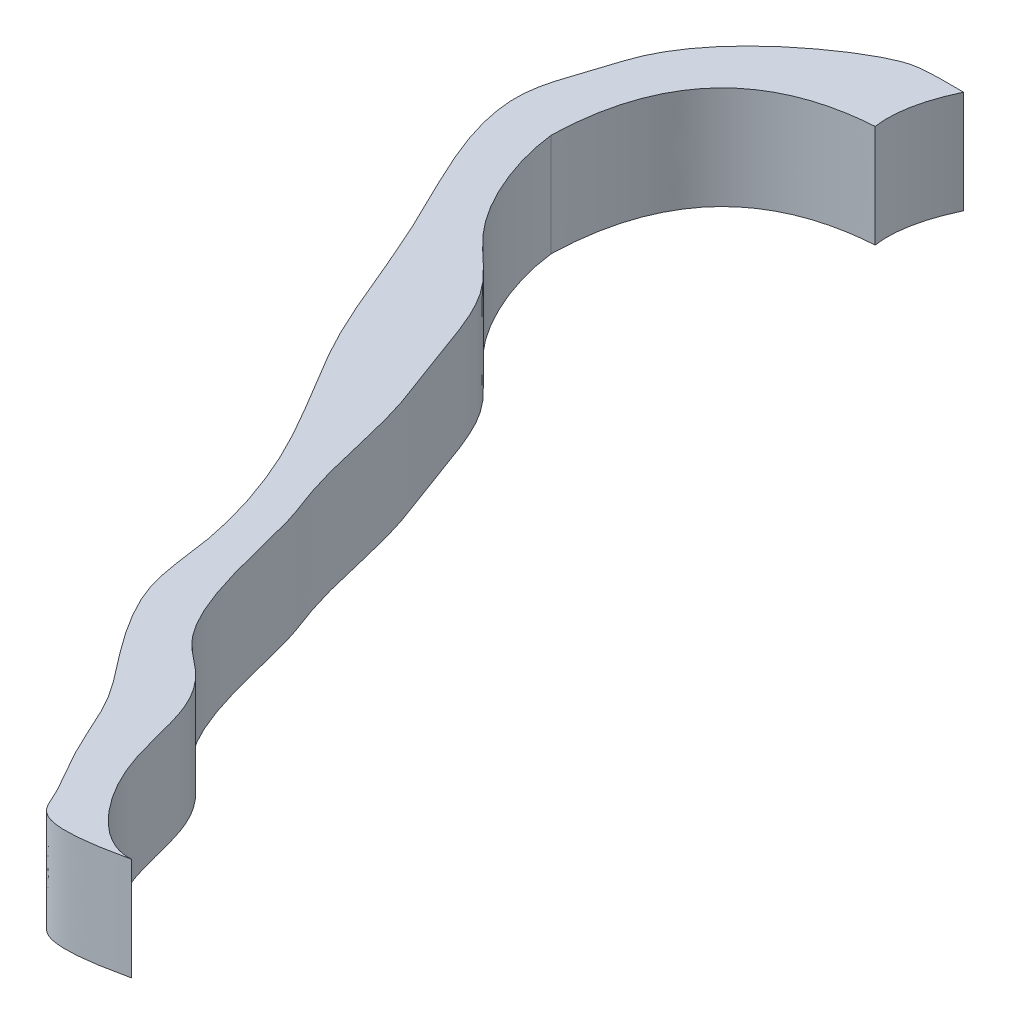
SolidWorks part; units mm, degrees
ref_plane "Front Plane" through (0, 0, 0) normal (0, 0, 1) x (1, 0, 0)
ref_plane "Top Plane" through (0, 0, 0) normal (0, 1, 0) x (1, 0, 0)
ref_plane "Right Plane" through (0, 0, 0) normal (1, 0, 0) x (0, 0, -1)
sketch "Sketch1" plane through (0, 0, 0) normal (0, 1, 0) x (1, 0, 0)
  line L0 (132.9208, 498.8792) -> (664.6039, 498.8792) construction
  spline S0 degree 3 poles (47.4452, 177.9518) (47.0254, 174.6028) (51.7593, 173.3412) (58.5168, 175.9883) (66.5294, 178.5609) (74.6759, 180.5916) (83.6389, 180.9303) (93.9024, 184.3691) (101.5901, 172.2989) (95.3588, 160.0205) (107.8833, 156.8361) (105.1716, 146.4959) (105.9458, 141.0781) (105.7573, 137.4199) knots 0 0 0 0 0.06805 0.126735 0.221277 0.325873 0.379658 0.499724 0.610693 0.730784 0.814837 0.89369 1 1 1 1
  spline S1 degree 3 poles (155.7138, 185.222) (155.4259, 173.1007) (140.4833, 166.9041) (118.937, 172.6125) (115.1926, 160.3303) (115.3483, 149.6177) (115.4446, 134.451) (112.0454, 122.272) (110.8252, 106.92) (107.256, 97.0985) (104.2872, 85.0571) (101.3268, 80.6207) (98.3712, 78.2317) knots 0 0 0 0 0.208505 0.326502 0.372957 0.455667 0.565003 0.69472 0.729434 0.891839 0.917523 1 1 1 1
  spline S2 degree 3 poles (101.3548, 63.7794) (107.1178, 76.7217) (120.4734, 89.8974) (142.3175, 99.8069) (151.7631, 112.7172) (156.6801, 127.2081) (155.0264, 140.7672) (165.9474, 153.3802) (166.4727, 165.3798) (166.4755, 181.7719) (162.7822, 182.2458) (155.7138, 185.222) knots 0 0 0 0 0.265264 0.365208 0.471004 0.575449 0.659468 0.752228 0.920298 0.960402 1 1 1 1
  spline S3 degree 3 poles (155.7138, 185.222) (143.3424, 186.5142) (135.7629, 190.1238) (119.6774, 191.4927) (117.3842, 188.1181) (119.1021, 183.0572) (117.4691, 176.1578) (109.7608, 174.5784) (104.9249, 180.5533) (105.8438, 189.0401) (96.5318, 187.2896) (86.9833, 184.162) (76.6059, 184.9315) (62.0967, 182.3633) (54.5279, 182.9985) (48.6859, 181.0303) knots 0 0 0 0 0.237105 0.256899 0.271012 0.314513 0.364495 0.396714 0.458476 0.498896 0.536122 0.613435 0.730761 0.758905 0.894881 0.894881 0.894881 0.894881
  spline S4 degree 3 poles (84.9542, 23.3748) (72.9575, 20.6745) (71.9674, 25.3606) (66.9703, 32.7264) (63.4633, 41.9395) (58.2122, 48.0409) (50.9968, 58.5561) (50.556, 70.2906) (44.9009, 87.4175) (33.1092, 103.9114) (26.3976, 123.9499) (14.0657, 144.8797) (18.6923, 155.8246) (22.3599, 168.9734) (39.2401, 181.2367) (43.1213, 181.0681) (48.6859, 181.0303) knots 0 0 0 0 0.04448 0.090013 0.138443 0.188153 0.244036 0.300209 0.390948 0.496437 0.613722 0.738952 0.786998 0.806175 0.930725 1 1 1 1
  spline S5 degree 2 poles (24.0375, 145.517) (24.6154, 168.8223) (46.572, 170.2544) knots 0 0 0 1 1 1
  spline S6 degree 3 poles (-2.5807, 150.5978) (25.3813, 187.2619) (71.2737, 199.7007) (119.1491, 205.3389) (188.8296, 188.5694) (163.6488, 122.953) (140.6923, 82.7557) (115.9514, 49.3428) (100.949, 22.7917) (69.9866, 8.4884) (58.9808, 34.5354) (42.6701, 50.0351) (32.6824, 78.02) (22.4132, 112.2265) (-2.5807, 150.5978) (25.3813, 187.2619) (71.2737, 199.7007) knots -0.214288 -0.144168 -0.056107 0 0.077118 0.196257 0.282165 0.391017 0.484824 0.558197 0.611423 0.659102 0.699139 0.739781 0.785712 0.855832 0.943893 1 1.077118 1.196257 1.282165 only from (24.0375, 181.0303) to (24.0375, 181.0303)
  spline S7 degree 3 poles (105.7573, 137.4199) (99.2152, 145.5617) (84.8034, 152.6035) (58.8818, 155.8466) (41.1998, 165.1008) (48.6859, 181.0303) knots 0 0 0 0 0.386611 0.562828 1 1 1 1
  spline S8 degree 3 poles (24.0375, 145.517) (24.2622, 143.639) (25.4171, 138.1348) (30.0077, 128.3576) (39.7991, 121.1152) (43.2129, 110.1463) (48.655, 97.0574) (49.9673, 86.7279) (54.646, 75.4111) (57.5935, 57.5488) (72.352, 47.8516) (69.1404, 35.825) (82.724, 21.3135) (91.461, 26.0846) (99.36, 34.146) (106.4591, 48.0552) (101.5336, 62.2605) (98.8404, 74.4776) (96.8682, 87.5544) (101.8022, 102.1432) (102.7904, 119.2975) (104.336, 130.4469) (105.7536, 137.4018) (105.7573, 137.4199) knots 0.084883 0.084883 0.084883 0.084883 0.10777 0.154078 0.187829 0.232552 0.269709 0.335229 0.347597 0.388302 0.400297 0.462464 0.490432 0.503111 0.523547 0.568461 0.596541 0.621395 0.653634 0.683153 0.723781 0.766209 0.766319 0.766319 0.766319 0.766319
extrude "Boss-Extrude1" add sketch "Sketch1" along normal blind 15 contours S8 S5 S7 S4
